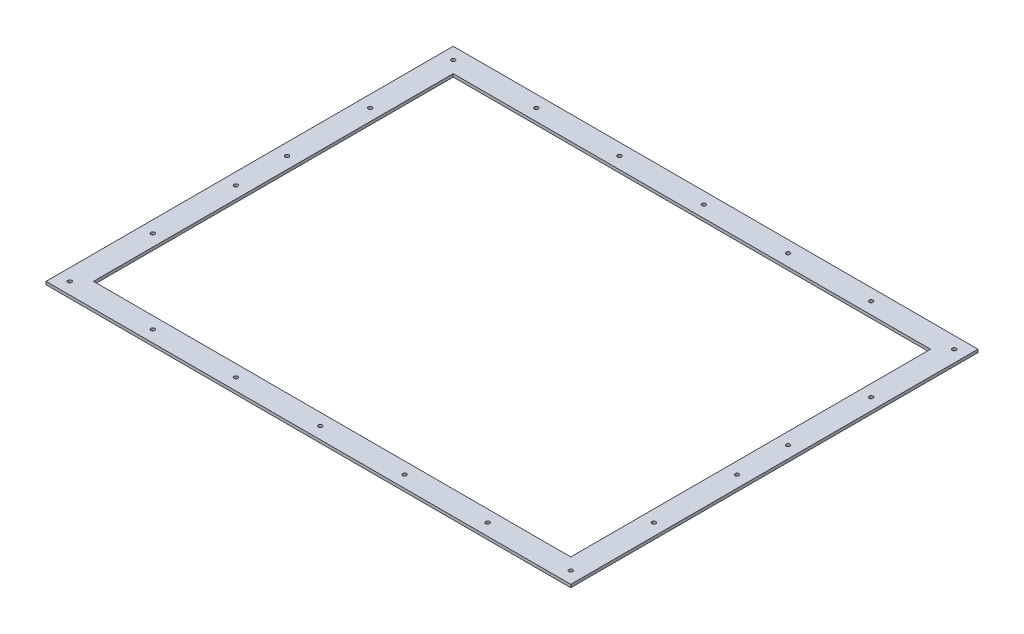
SolidWorks part; units mm, degrees
material "AISI 304"
ref_plane "Piano frontale" through (0, 0, 0) normal (0, 0, 1) x (1, 0, 0)
ref_plane "Piano superiore" through (0, 0, 0) normal (0, 1, 0) x (1, 0, 0)
ref_plane "Piano destro" through (0, 0, 0) normal (1, 0, 0) x (0, 0, -1)
sketch "Schizzo1" plane through (0, 0, 0) normal (0, 1, 0) x (1, 0, 0)
  line L0 (-442, -343) -> (-442, 343)
  line L1 (402, -303) -> (-402, -303)
  line L2 (402, -303) -> (402, 303)
  line L3 (402, 303) -> (-402, 303)
  line L4 (-402, -303) -> (-402, 303)
  line L5 (442, 343) -> (-442, 343)
  line L6 (442, -343) -> (442, 343)
  line L7 (442, -343) -> (-442, -343)
  point P0 (0, 0)
  dimension "D1" = 40
extrude "Estrusione-Estrusione1" add sketch "Schizzo1" along normal mid plane 5
sketch "Schizzo2" plane through (0, 2.5, 0) normal (0, 1, 0) x (1, 0, 0)
  line L10 (0, -400) -> (0, 400) construction
  line L11 (500, 0) -> (-500, 0) construction
  line L14 (-422, -323) -> (422, -323)
  line L15 (422, -323) -> (422, 323)
  line L16 (422, 323) -> (-422, 323)
  line L17 (-422, 323) -> (-422, -323)
  line L18 (-422, -323) -> (422, -323) construction
  line L19 (422, -323) -> (422, 323) construction
  line L20 (422, 323) -> (-422, 323) construction
  line L21 (-422, 323) -> (-422, -323) construction
  circle A0 centre (-422, 323) radius 3.25
  circle A1 centre (422, 323) radius 3.25
  circle A2 centre (422, -323) radius 3.25
  circle A3 centre (-422, -323) radius 3.25
  circle A4 centre (-282, 323) radius 3.25
  circle A5 centre (-142, 323) radius 3.25
  circle A6 centre (0, 323) radius 3.25
  circle A7 centre (142, 323) radius 3.25
  circle A8 centre (282, 323) radius 3.25
  circle A9 centre (282, -323) radius 3.25
  circle A10 centre (142, -323) radius 3.25
  circle A11 centre (0, -323) radius 3.25
  circle A12 centre (-142, -323) radius 3.25
  circle A13 centre (-282, -323) radius 3.25
  circle A15 centre (-422, 183) radius 3.25
  circle A16 centre (-422, 43) radius 3.25
  circle A17 centre (-422, -43) radius 3.25
  circle A18 centre (-422, -183) radius 3.25
  circle A19 centre (422, -183) radius 3.25
  circle A20 centre (422, -43) radius 3.25
  circle A21 centre (422, 43) radius 3.25
  circle A22 centre (422, 183) radius 3.25
  point P4 (0, 0)
  point P7 (0, 0)
  dimension "D2" = 3
  dimension "D3" = 3
  dimension "D1" = 20
extrude "Taglio-Estrusione1" cut sketch "Schizzo2" against normal through all
